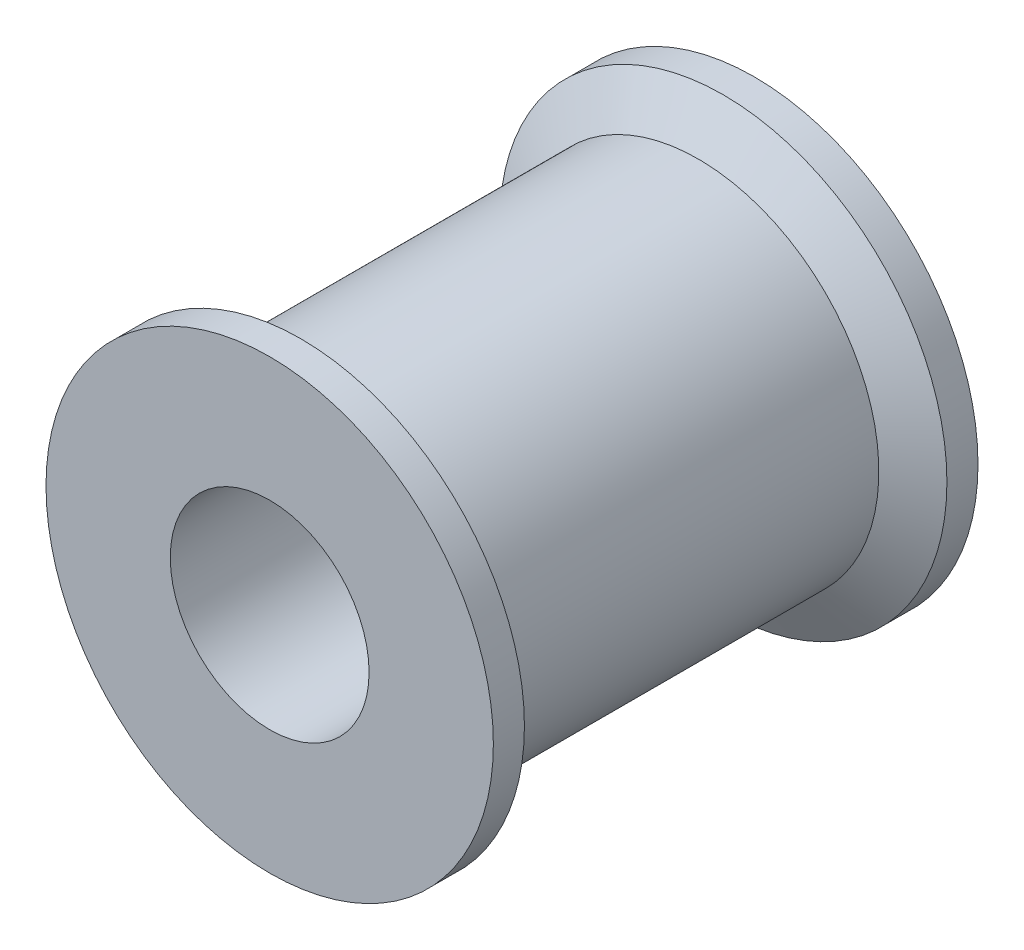
SolidWorks part; units mm, degrees
ref_plane "Přední rovina" through (0, 0, 0) normal (0, 0, 1) x (1, 0, 0)
ref_plane "Horní rovina" through (0, 0, 0) normal (0, 1, 0) x (1, 0, 0)
ref_plane "Pravá rovina" through (0, 0, 0) normal (1, 0, 0) x (0, 0, -1)
sketch "Skica1" plane through (0, 0, 0) normal (1, 0, 0) x (0, 0, -1)
  line L0 (0, 0) -> (-31.8265, 0) construction
  line L1 (0, 4) -> (0, 4.75)
  line L2 (-6.5, 9) -> (-7.75, 9)
  line L3 (-7.75, 9) -> (-8.75, 7.26)
  line L4 (-8.75, 7.26) -> (-23.75, 7.26)
  line L5 (-23.75, 7.26) -> (-24.75, 9)
  line L6 (-24.75, 9) -> (-26, 9)
  line L7 (-26, 9) -> (-26, 4)
  line L8 (-24.75, 9) -> (-7.75, 9) construction
  line L9 (-26, 4) -> (0, 4)
  line L10 (-16.25, 9) -> (-16.25, 7.26) construction
  line L11 (-6.5, 9) -> (-6.5, 4.75)
  line L12 (-6.5, 4.75) -> (0, 4.75)
  dimension "D1" = 18
  dimension "D2" = 14.52
  dimension "D3" = 26
  dimension "D4" = 15
  dimension "D5" = 17
  dimension "D6" = 8
  dimension "D7" = 19.5
  dimension "D8" = 3.26
  dimension "D9" = 9.5
revolve "Rotovat1" add sketch "Skica1" angle 360 about L0
sketch "Skica2" plane through (0, 0, 0) normal (0, 1, 0) x (1, 0, 0)
  line L1 (-4.75, 0) -> (4.75, 0)
  line L2 (-4.75, 0) -> (-4.75, -6.5)
  line L3 (-4.75, -6.5) -> (4.75, -6.5)
  line L4 (4.75, 0) -> (4.75, -6.5)
extrude "Odebrat vysunutím1" cut sketch "Skica2" against normal through all and the other way through all
move or copy body "Tělo-Přesunout/kopírovat1" [suppressed] bodies to move or copy 102
